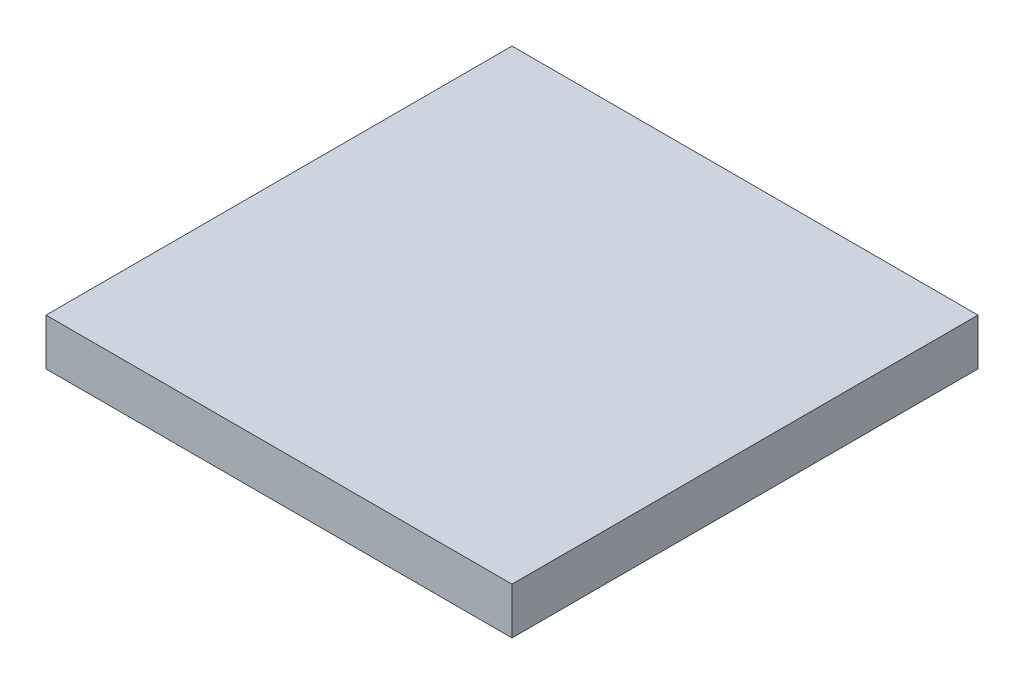
SolidWorks part; units mm, degrees
ref_plane "前视基准面" through (0, 0, 0) normal (0, 0, 1) x (1, 0, 0)
ref_plane "上视基准面" through (0, 0, 0) normal (0, 1, 0) x (1, 0, 0)
ref_plane "右视基准面" through (0, 0, 0) normal (1, 0, 0) x (0, 0, -1)
other "Configuration Table"
sketch "草图1" plane through (0, 0, 0) normal (0, 1, 0) x (1, 0, 0)
  line L1 (0, 0) -> (100, 0)
  line L2 (0, 0) -> (0, 100)
  line L3 (0, 100) -> (100, 100)
  line L4 (100, 0) -> (100, 100)
  dimension "D1" = 100
  dimension "D2" = 100
extrude "凸台-拉伸1" add sketch "草图1" along normal blind 10
